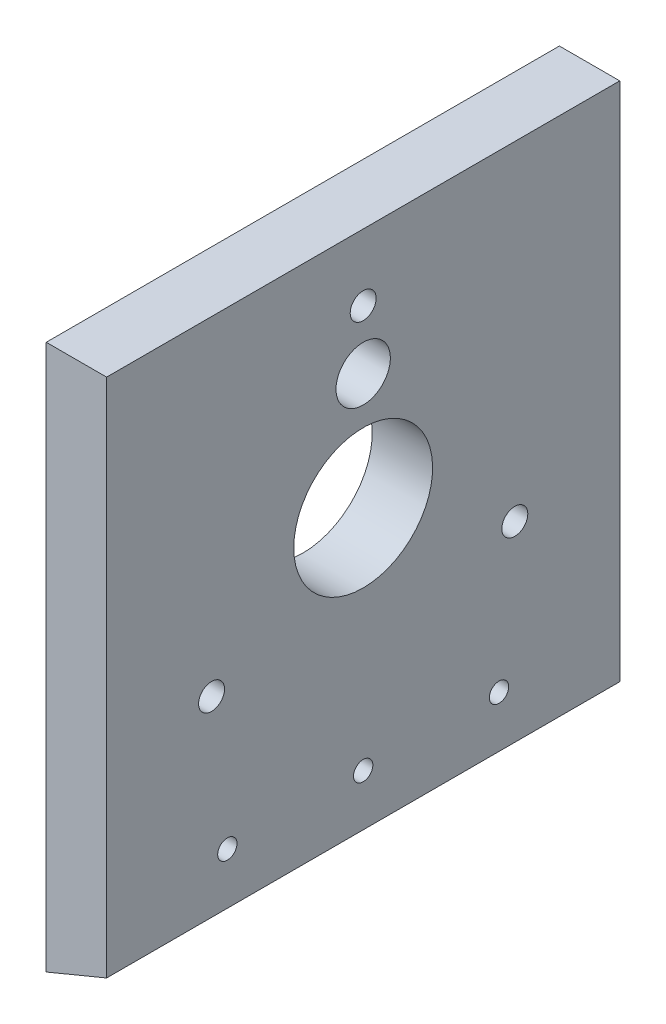
SolidWorks part; units mm, degrees
ref_plane "Front Plane" through (0, 0, 0) normal (0, 0, 1) x (1, 0, 0)
ref_plane "Top Plane" through (0, 0, 0) normal (0, 1, 0) x (1, 0, 0)
ref_plane "Right Plane" through (0, 0, 0) normal (1, 0, 0) x (0, 0, -1)
sketch "Sketch2" plane through (0, 0, 0) normal (0, 0, 1) x (1, 0, 0)
  line L0 (0, 0) -> (0, 86.2)
  line L1 (0, 86.2) -> (-10, 86.2)
  line L2 (-10, 86.2) -> (-10, -4.1421)
  line L3 (-10, -4.1421) -> (0, 0)
  dimension "D1" = 86.2
  dimension "D2" = 247.5
  dimension "D3" = 10
extrude "Boss-Extrude1" add sketch "Sketch2" along normal blind 85
sketch "Sketch3" plane through (-10, 0, 0) normal (-1, 0, 0) x (0, 0, 1)
  line L0 (42.5, 86.2) -> (42.5, -4.1421) construction
  line L1 (85, 86.2) -> (0, 86.2) construction
  line L2 (85, -4.1421) -> (0, -4.1421) construction
  circle A0 centre (42.5, 46.2) radius 11.5
  circle A1 centre (42.5, 65.45) radius 4.5
  circle A2 centre (42.5, 75.2) radius 2.15
  circle A3 centre (67.6147, 31.7) radius 2.15
  circle A4 centre (17.3853, 31.7) radius 2.15
  point P19 (42.5, 46.2)
  dimension "D1" = 23
  dimension "D3" = 9
  dimension "D5" = 4.3
  dimension "D2" = 40
  dimension "D4" = 19.25
  dimension "D6" = 29
  dimension "D7" = 3
extrude "Cut-Extrude1" cut sketch "Sketch3" against normal blind 85
sketch "Sketch4" plane through (0, 0, 0) normal (1, 0, 0) x (0, 0, -1)
  line L0 (-85, 0) -> (0, 0) construction
  line L1 (-85, 0) -> (-85, 86.2) construction
  line L2 (0, 0) -> (0, 86.2) construction
  circle A0 centre (-65, 8.5) radius 1.6
  circle A1 centre (-20, 8.5) radius 1.6
  circle A2 centre (-42.5, 8.5) radius 1.6
  dimension "D1" = 3.2
  dimension "D2" = 3.2
  dimension "D7" = 3.2
  dimension "D3" = 8.5
  dimension "D4" = 8.5
  dimension "D5" = 20
  dimension "D6" = 20
  dimension "D8" = 8.5
  dimension "D9" = 42.5
extrude "Cut-Extrude2" cut sketch "Sketch4" against normal blind 85
